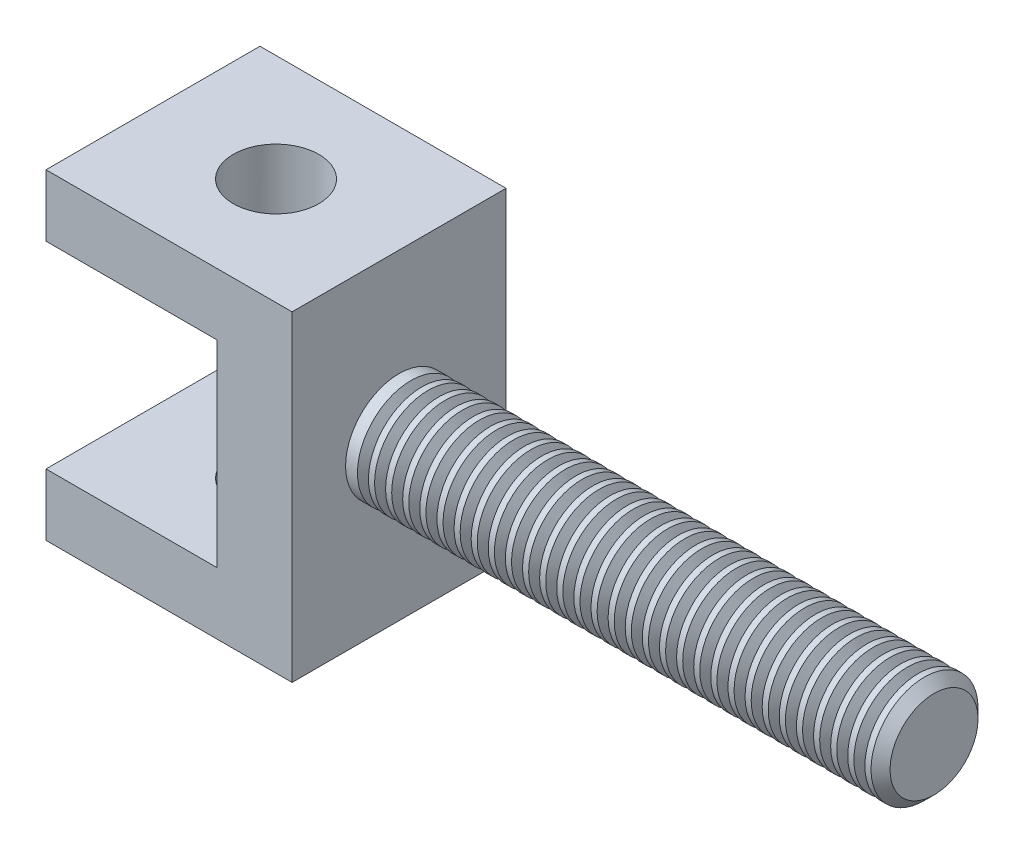
SolidWorks part; units mm, degrees
ref_plane "Front Plane" through (0, 0, 0) normal (0, 0, 1) x (1, 0, 0)
ref_plane "Top Plane" through (0, 0, 0) normal (0, 1, 0) x (1, 0, 0)
ref_plane "Right Plane" through (0, 0, 0) normal (1, 0, 0) x (0, 0, -1)
other "Configuration Table"
sketch "BaseHeadSke" plane through (0, 0, 0) normal (1, 0, 0) x (0, 0, -1)
  line L1 (0, 4.6188) -> (-4, 2.3094)
  line L2 (-4, 2.3094) -> (-4, -2.3094)
  line L3 (-4, -2.3094) -> (0, -4.6188)
  line L4 (0, -4.6188) -> (4, -2.3094)
  line L5 (4, -2.3094) -> (4, 2.3094)
  line L6 (4, 2.3094) -> (0, 4.6188)
  circle A0 centre (0, 0) radius 4 construction
  dimension "Width_flats" = 8
extrude "BaseHead" add sketch "BaseHeadSke" along normal blind 3.5
sketch "HeadChamferSke" plane through (0, 0, 0) normal (0, 0, 1) x (1, 0, 0)
  line L0 (0, 0) -> (108.1848, 0) construction
  line L1 (0, 2.3094) -> (0, -2.3094) construction
  line L2 (0, 4.6188) -> (0, 4)
  line L3 (0, 4) -> (0.3573, 4.6188)
  line L4 (0.3573, 4.6188) -> (0, 4.6188)
  line L7 (3.5, 4.6188) -> (0, 4.6188) construction
  dimension "Angle_Chamfer_Head" = 30
revolve "HeadChamfer" cut sketch "HeadChamferSke" angle 360 about L0
sketch "BodySke" plane through (0, 0, 0) normal (0, 0, 1) x (1, 0, 0)
  line L0 (0, 0) -> (440.8544, 0) construction
  line L1 (0, 0) -> (0, 2.5)
  line L3 (0, 3.4641) -> (0, 0) construction
  line L4 (0, 2.5) -> (28.055, 2.5)
  line L5 (28.055, 2.5) -> (28.5, 2.055)
  line L6 (28.5, 2.055) -> (28.5, 0)
  line L7 (28.5, 0) -> (0, 0)
  line L8 (4.3, 0) -> (4.3, 20.794) construction
  line L9 (3.5, 2.3094) -> (3.5, -2.3094) construction
  line L10 (3.5, 0) -> (3.5, 20.794) construction
  dimension "Thread_minor" = 4.11
  dimension "Advance" = 0.8
  dimension "Length" = 25
  dimension "Diameter" = 5
  dimension "Body_Chamfer_Angle" = 45
  dimension "Thread_length" = 25
revolve "BaseBody" add sketch "BodySke" angle 360 about L0
cosmetic thread "ThreadCosmetic" [suppressed] parameters "Thread_minor"=4.11
sketch "BearingFaceSke" plane through (0, 0, 0) normal (0, 0, 1) x (1, 0, 0)
  line L0 (0, 0) -> (414.2241, 0) construction
  line L1 (3.5, 4.6188) -> (3.5, 2.3094) construction
  line L2 (3.5, 4) -> (3, 4)
  line L3 (3.5, 4) -> (3.5, 14)
  line L4 (3.5, 14) -> (3, 14)
  line L5 (3, 4) -> (3, 14)
  dimension "D1" = 10
  dimension "D2" = 8
  dimension "Bearing_height" = 0.5
revolve "BearingFace" [suppressed] cut sketch "BearingFaceSke" angle 360 about L0
fillet "HeadFillet" [suppressed] radius 0.2
sketch "ThdSchSke" plane through (0, 0, 0) normal (0, 0, 1) x (1, 0, 0)
  line L0 (0, 0) -> (453.2163, 0) construction
  line L1 (27.255, 3.0138) -> (27.255, 2.5)
  line L2 (27.255, 3.0138) -> (27.7688, 3.0138)
  line L3 (27.7688, 3.0138) -> (27.7688, 2.5)
  line L4 (27.7688, 2.5) -> (27.5119, 2.055)
  line L5 (27.5119, 2.055) -> (27.255, 2.5)
  dimension "D1" = 0.8
revolve "ThreadSchematic" cut sketch "ThdSchSke" angle 360 about L0
pattern_linear "ThdSchPat" count 30 spacing 0.8 along (-1, 0, 0) of "ThreadSchematic"
ref_plane "Plane1" through (0, 0, 0) normal (0, 0, 1) x (1, 0, 0)
sketch "Sketch1" plane through (0, 0, 0) normal (0, 0, 1) x (1, 0, 0)
  line L4 (-8, 7.5) -> (3.5, 7.5)
  line L9 (-8.1684, 0) -> (5.9119, 0) construction
  line L10 (5.9119, 2.055) -> (5.9119, -2.055) construction
  line L11 (0, 4.6081) -> (0, -4.6081)
  line L12 (0, -4.6081) -> (-8, -4.6081)
  line L13 (-8, -4.6081) -> (-8, -7.5)
  line L14 (-8, -7.5) -> (3.5, -7.5)
  line L15 (3.5, -7.5) -> (3.5, 7.5)
  line L16 (3.5, 2.3094) -> (3.5, -2.3094) construction
  line L17 (-8, 4.6081) -> (-8, 7.5)
  line L18 (0, 4.6081) -> (-8, 4.6081)
  point P7 (3.5, 0)
  point P16 (0, 0)
  dimension "D1" = 4.6081
  dimension "D2" = 8
  dimension "D3" = 7.5
extrude "Boss-Extrude1" add sketch "Sketch1" along normal mid plane 10
sketch "Sketch3" plane through (0, -7.5, 0) normal (0, -1, 0) x (1, 0, 0)
  line L0 (-8, 5) -> (3.5, -5) construction
  line L1 (3.5, 5) -> (-8, -5) construction
  circle A0 centre (-2.25, 0) radius 2
extrude "Cut-Extrude1" cut sketch "Sketch3" against normal blind 17
equation "\"Thread_minor@ThreadCosmetic\" = \"Thread_minor@BodySke\""
equation "\"D2@BearingFaceSke\" = \"Width_flats@BaseHeadSke\""
equation "\"D1@ThdSchSke\" = \"Advance@BodySke\""
equation "\"Advance@ThdSchPat\" = \"Advance@BodySke\""
equation "\"Tooth_Num@ThdSchPat\" =  int( \"Thread_length@BodySke\" / \"Advance@BodySke\" ) - 1 "
